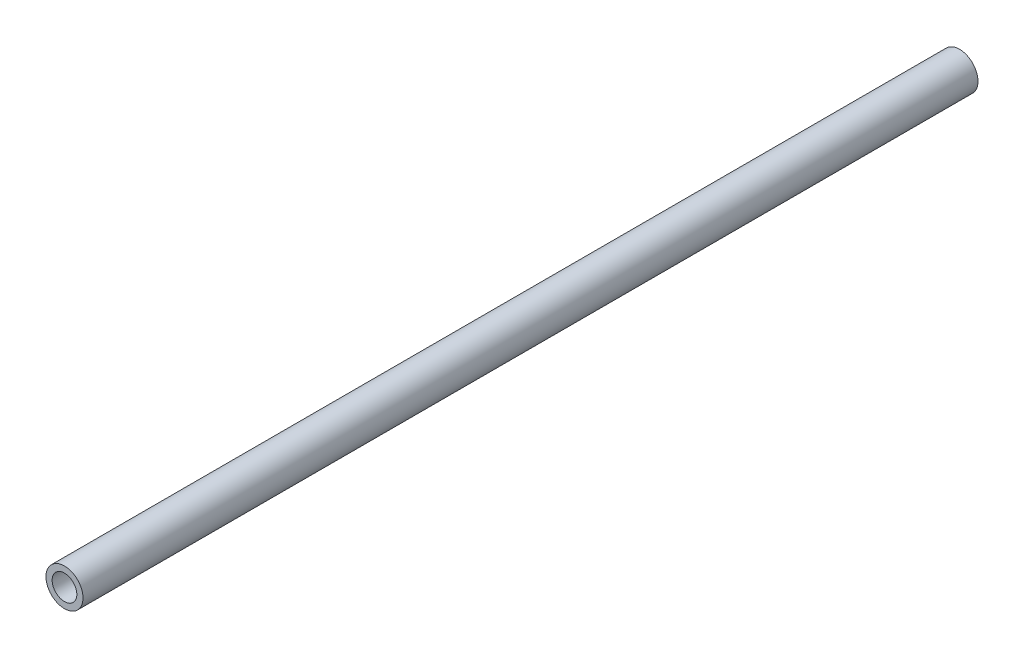
SolidWorks part; units mm, degrees
ref_plane "Front Plane" through (0, 0, 0) normal (0, 0, 1) x (1, 0, 0)
ref_plane "Top Plane" through (0, 0, 0) normal (0, 1, 0) x (1, 0, 0)
ref_plane "Right Plane" through (0, 0, 0) normal (1, 0, 0) x (0, 0, -1)
sketch "Sketch1" plane through (0, 0, 0) normal (0, 0, 1) x (1, 0, 0)
  circle A0 centre (0, 0) radius 3
  circle A1 centre (0, 0) radius 2
  dimension "D1" = 6
  dimension "D2" = 4
extrude "Boss-Extrude1" add sketch "Sketch1" along normal blind 145
